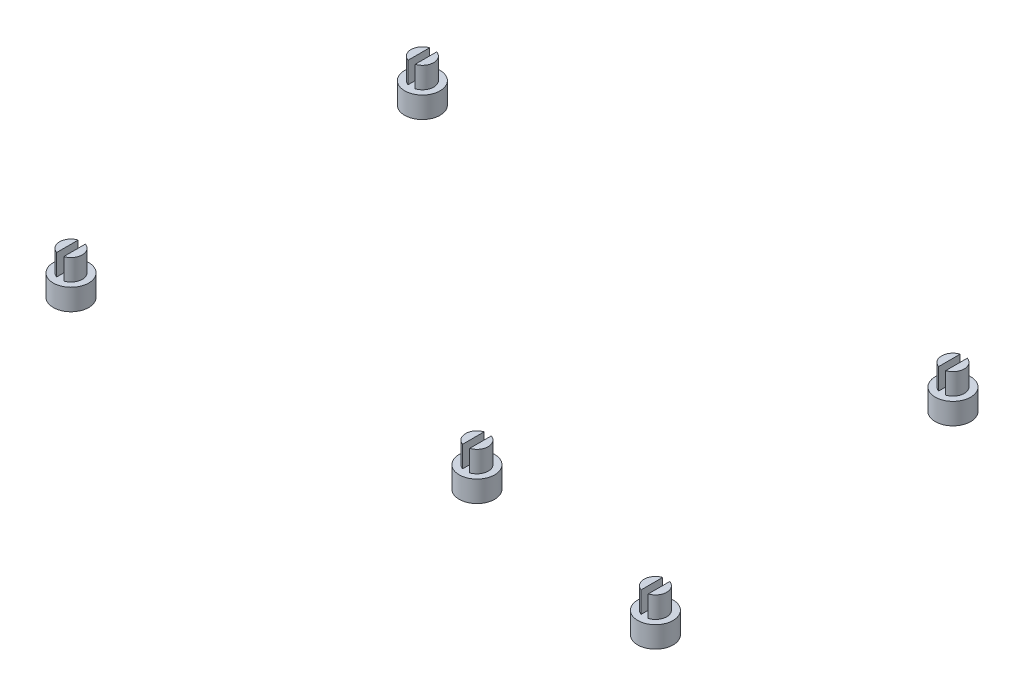
SolidWorks part; units mm, degrees
ref_plane "Front Plane" through (0, 0, 0) normal (0, 0, 1) x (1, 0, 0)
ref_plane "Top Plane" through (0, 0, 0) normal (0, 1, 0) x (1, 0, 0)
ref_plane "Right Plane" through (0, 0, 0) normal (1, 0, 0) x (0, 0, -1)
sketch "Sketch3" plane through (0, 25.0299, 0) normal (0, 1, 0) x (1, 0, 0)
  circle A0 centre (-17.6293, -15.3915) radius 2.5
  circle A1 centre (57.2707, -15.3915) radius 2.5
  circle A2 centre (63.5707, -63.6915) radius 2.5
  circle A3 centre (33.1707, -58.4915) radius 2.5
  circle A4 centre (-18.9293, -63.6915) radius 2.5
  circle A5 centre (-18.9293, -63.6915) radius 1.6 construction
  circle A6 centre (-17.6293, -15.3915) radius 1.6 construction
  point P3 (0, 0)
  point P16 (-9.77, -61.1294)
  point P19 (-13.0462, -8.476)
  point P22 (0, 0)
  point P23 (0, 0)
  point P24 (0, 0)
  point P25 (57.2707, -15.3915)
  point P27 (33.1707, -58.4915)
  point P29 (63.5707, -63.6915)
  dimension "D1" = 5
extrude "Boss-Extrude2" add sketch "Sketch3" along normal blind 3
sketch "Sketch1" plane through (0, 25.0299, 0) normal (0, 1, 0) x (1, 0, 0)
  line L0 (57.2707, -13.7915) -> (57.2707, -16.9915) construction
  line L1 (63.5707, -62.0915) -> (63.5707, -65.2915) construction
  line L2 (56.7707, -13.7915) -> (56.7707, -16.9915)
  line L3 (63.0707, -62.0915) -> (63.0707, -65.2915)
  line L4 (64.0707, -62.0915) -> (64.0707, -65.2915)
  line L6 (-17.1293, -16.9114) -> (-17.1293, -13.8716)
  line L8 (-18.1293, -16.9114) -> (-18.1293, -13.8716)
  line L9 (57.7707, -13.7915) -> (57.7707, -16.9915)
  line L10 (33.1707, -56.8915) -> (33.1707, -60.0915)
  line L11 (-18.9293, -62.0915) -> (-18.9293, -65.2915) construction
  line L12 (32.6707, -56.8915) -> (32.6707, -60.0915)
  line L13 (-19.4293, -62.0915) -> (-19.4293, -65.2915)
  line L14 (33.6707, -56.8915) -> (33.6707, -60.0915)
  line L15 (-18.4293, -62.0915) -> (-18.4293, -65.2915)
  line L17 (-17.1293, -16.9114) -> (-18.1293, -13.8716) construction
  line L18 (-17.1293, -13.8716) -> (-18.1293, -16.9114) construction
  circle A10 centre (-17.6293, -15.3915) radius 1.6
  circle A11 centre (-17.6293, -15.3915) radius 1.6 construction
  circle A12 centre (57.2707, -15.3915) radius 1.6
  circle A13 centre (57.2707, -15.3915) radius 1.6 construction
  circle A14 centre (63.5707, -63.6915) radius 1.6
  circle A15 centre (63.5707, -63.6915) radius 1.6 construction
  circle A16 centre (33.1707, -58.4915) radius 1.6
  circle A17 centre (-18.9293, -63.6915) radius 1.6
  circle A18 centre (-18.9293, -63.6915) radius 1.6 construction
  dimension "D4" = 0.5
  dimension "D3" = 0.5
  dimension "D5" = 0.5
  dimension "D6" = 0.5
  dimension "D1" = 1
  dimension "D2" = 0.5
  dimension "D7" = 0.5
extrude "Boss-Extrude1" add sketch "Sketch1" along normal blind 3 from surface at 3 contours L6 A10 | L8 A10 | L4 A14 | L3 A14 | L14 A16 | L12 A16 | L15 A17 | L13 A17 | L9 A12 | L2 A12
other "Join1"
other "mega holder<1>@Arduino Mega in the holder"
